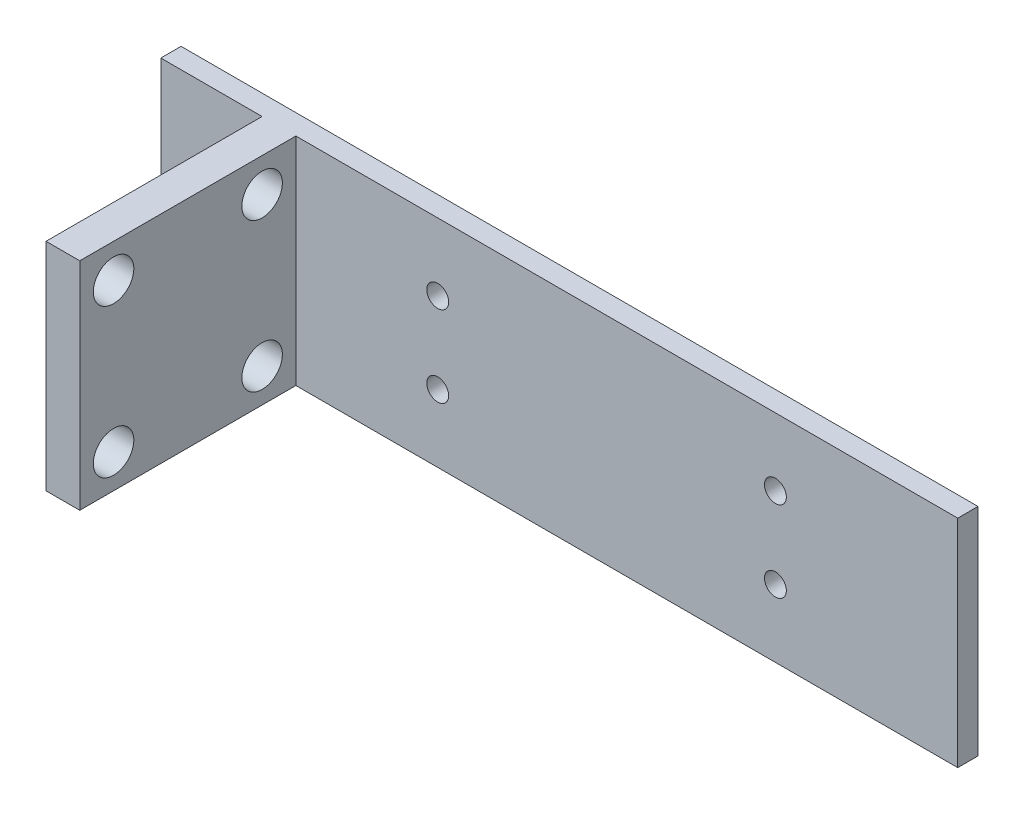
SolidWorks part; units mm, degrees
ref_plane "前视基准面" through (0, 0, 0) normal (0, 0, 1) x (1, 0, 0)
ref_plane "上视基准面" through (0, 0, 0) normal (0, 1, 0) x (1, 0, 0)
ref_plane "右视基准面" through (0, 0, 0) normal (1, 0, 0) x (0, 0, -1)
sketch "草图1" plane through (0, 0, 0) normal (0, 0, 1) x (1, 0, 0)
  line L1 (-71.2816, 22.717) -> (46.7184, 22.717)
  line L2 (-71.2816, 22.717) -> (-71.2816, -9.283)
  line L3 (-71.2816, -9.283) -> (46.7184, -9.283)
  line L4 (46.7184, 22.717) -> (46.7184, -9.283)
  dimension "D1" = 118
  dimension "D2" = 32
extrude "凸台-拉伸1" add sketch "草图1" along normal blind 3
sketch "草图2" plane through (0, 0, 3) normal (0, 0, 1) x (1, 0, 0)
  line L0 (-71.2816, 22.717) -> (-71.2816, -9.283) construction
  line L1 (46.7184, 22.717) -> (-71.2816, 22.717) construction
  line L2 (-71.2816, -9.283) -> (46.7184, -9.283) construction
  circle A0 centre (-30.2816, 12.717) radius 1.62
  circle A1 centre (-30.2816, 0.717) radius 1.62
  circle A2 centre (19.7184, 12.717) radius 1.62
  circle A3 centre (19.7184, 0.717) radius 1.62
  dimension "D1" = 3.24
  dimension "D2" = 41
  dimension "D3" = 10
  dimension "D4" = 3.24
  dimension "D5" = 10
  dimension "D6" = 41
  dimension "D7" = 3.24
  dimension "D8" = 50
  dimension "D9" = 3.24
extrude "切除-拉伸1" cut sketch "草图2" against normal blind 3
sketch "草图3" plane through (0, 0, 3) normal (0, 0, 1) x (1, 0, 0)
  line L0 (-71.2816, -9.283) -> (46.7184, -9.283) construction
  line L1 (-56.2816, 22.717) -> (-51.2816, 22.717)
  line L2 (-56.2816, 22.717) -> (-56.2816, -9.283)
  line L3 (-56.2816, -9.283) -> (-51.2816, -9.283)
  line L4 (-51.2816, 22.717) -> (-51.2816, -9.283)
  line L5 (-71.2816, 22.717) -> (-71.2816, -9.283) construction
  dimension "D1" = 5
  dimension "D2" = 15
extrude "凸台-拉伸2" add sketch "草图3" along normal blind 32
sketch "草图4" plane through (-71.2816, 0, 0) normal (-1, 0, 0) x (0, 0, 1)
  line L0 (35, 22.717) -> (35, -9.283) construction
  line L1 (3, 22.717) -> (0, 22.717) construction
  line L2 (3, -9.283) -> (0, -9.283) construction
  line L3 (0, 22.717) -> (0, -9.283) construction
  circle A0 centre (30, 17.717) radius 3
  circle A1 centre (30, -4.283) radius 3
  circle A2 centre (8, 17.717) radius 3
  circle A3 centre (8, -4.283) radius 3
  dimension "D1" = 5
  dimension "D3" = 5
  dimension "D4" = 5
  dimension "D5" = 8
  dimension "D2" = 5
extrude "切除-拉伸2" cut sketch "草图4" against normal blind 32
